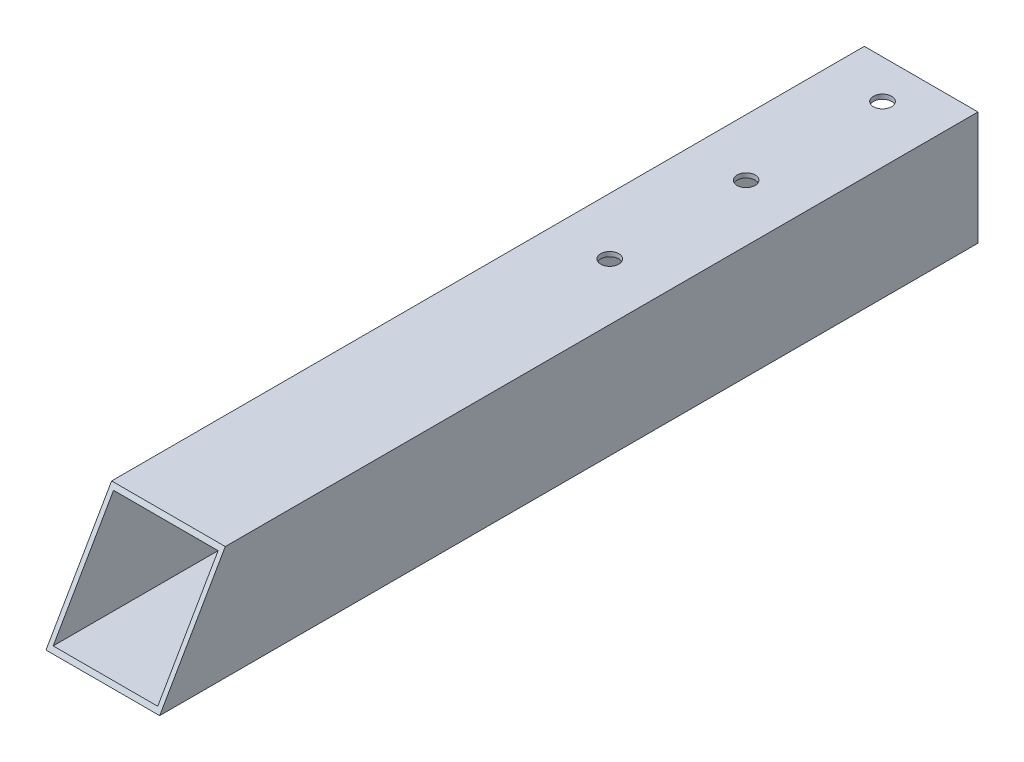
SolidWorks part; units mm, degrees
ref_plane "Front Plane" through (0, 0, 0) normal (0, 0, 1) x (1, 0, 0)
ref_plane "Top Plane" through (0, 0, 0) normal (0, 1, 0) x (1, 0, 0)
ref_plane "Right Plane" through (0, 0, 0) normal (1, 0, 0) x (0, 0, -1)
sketch "Sketch1" plane through (0, 0, 0) normal (0, 0, 1) x (1, 0, 0)
  line L0 (-11.5, -11.5) -> (11.5, -11.5)
  line L1 (-12.5, -12.5) -> (12.5, -12.5)
  line L2 (-12.5, -12.5) -> (-12.5, 12.5)
  line L3 (-12.5, 12.5) -> (12.5, 12.5)
  line L4 (12.5, -12.5) -> (12.5, 12.5)
  line L5 (-12.5, -12.5) -> (12.5, 12.5) construction
  line L6 (-12.5, 12.5) -> (12.5, -12.5) construction
  line L7 (11.5, -11.5) -> (11.5, 11.5)
  line L8 (-11.5, 11.5) -> (11.5, 11.5)
  line L9 (-11.5, -11.5) -> (-11.5, 11.5)
  point P0 (0, 0)
  dimension "D1" = 25
  dimension "D2" = 1
extrude "Boss-Extrude1" add sketch "Sketch1" along normal blind 180
sketch "Sketch2" plane through (12.5, 0, 0) normal (1, 0, 0) x (0, 0, -1)
  line L0 (-180, -12.5) -> (-165.5662, 12.5)
  line L1 (-180, 12.5) -> (0, 12.5) construction
  line L2 (-165.5662, 12.5) -> (-180, 12.5)
  line L3 (-180, 12.5) -> (-180, -12.5)
  dimension "D1" = 30
extrude "Cut-Extrude1" cut sketch "Sketch2" against normal through all
sketch "Sketch3" plane through (0, 12.5, 0) normal (0, 1, 0) x (1, 0, 0)
  line L0 (0, 0) -> (0, -165.5662) construction
  line L1 (-12.5, -165.5662) -> (12.5, -165.5662) construction
  line L3 (12.5, 0) -> (-12.5, 0) construction
  circle A0 centre (0, -8.5) radius 2
  circle A1 centre (0, -38.5) radius 2
  circle A2 centre (0, -68.5) radius 2
  dimension "D2" = 30
  dimension "D3" = 30
  dimension "D4" = 4
  dimension "D1" = 38.5
extrude "Cut-Extrude2" cut sketch "Sketch3" against normal up to next
